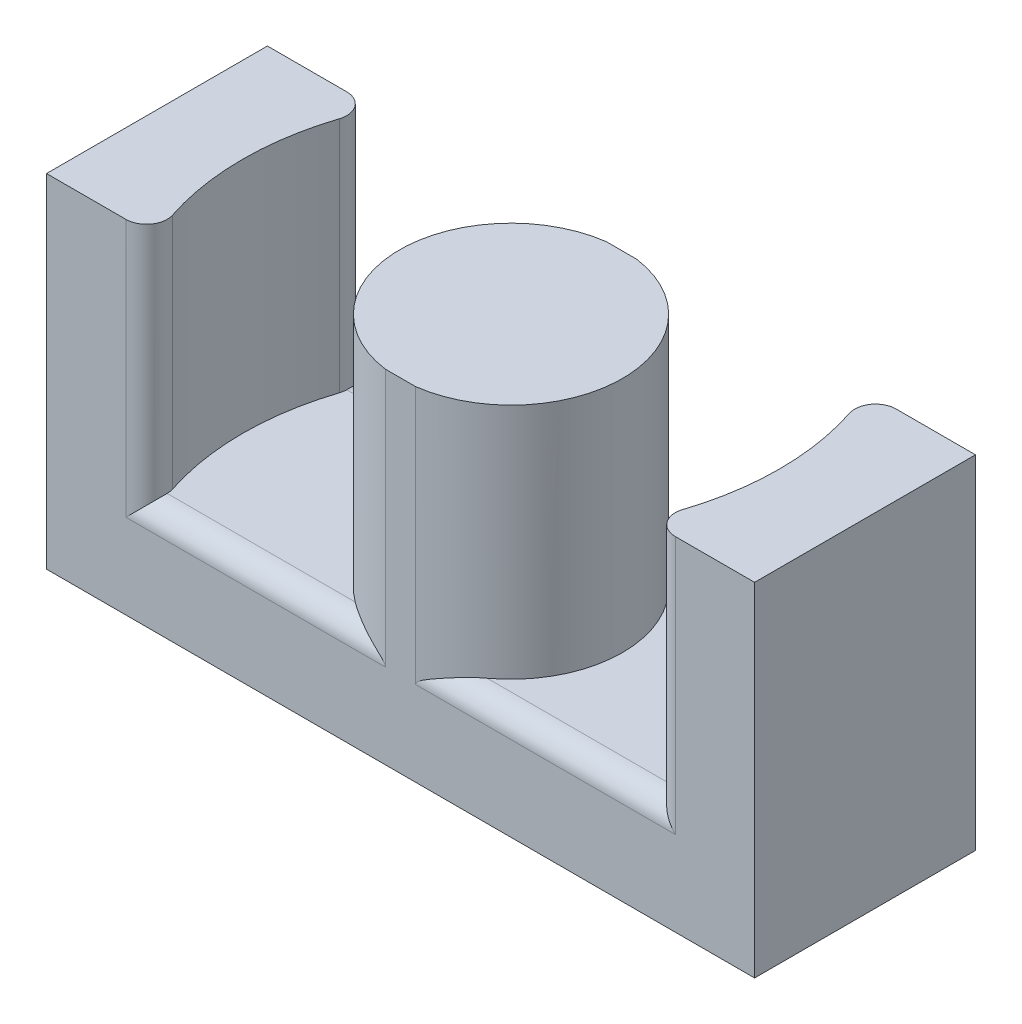
SolidWorks part; units mm, degrees
ref_plane "Front Plane" through (0, 0, 0) normal (0, 0, 1) x (1, 0, 0)
ref_plane "Top Plane" through (0, 0, 0) normal (0, 1, 0) x (1, 0, 0)
ref_plane "Right Plane" through (0, 0, 0) normal (1, 0, 0) x (0, 0, -1)
sketch "Sketch1" plane through (0, 0, 0) normal (0, 1, 0) x (1, 0, 0)
  line L0 (-22.3173, 0) -> (23.0727, 0) construction
  line L1 (11.8481, -5.35) -> (17.15, -5.35)
  line L2 (-17.15, 5.35) -> (-11.8481, 5.35)
  line L3 (-17.15, 5.35) -> (-17.15, -5.35)
  line L4 (-17.15, -5.35) -> (-11.8481, -5.35)
  line L5 (17.15, 5.35) -> (17.15, -5.35)
  line L6 (-17.15, 5.35) -> (-12.4102, 3.8714) construction
  line L7 (-17.15, -5.35) -> (-12.4102, -3.8714) construction
  line L8 (12.4102, -3.8714) -> (17.15, -5.35) construction
  line L9 (12.4102, 3.8714) -> (17.15, 5.35) construction
  line L10 (11.8481, 5.35) -> (17.15, 5.35)
  line L11 (-0.7331, 5.35) -> (0.7331, 5.35)
  line L12 (-5.155, 1.6081) -> (5.155, -1.6081) construction
  line L13 (-5.155, -1.6081) -> (5.155, 1.6081) construction
  line L14 (-0.7331, -5.35) -> (0.7331, -5.35)
  circle A0 centre (0, 0) radius 5.4
  arc A1 (-11.8481, 5.35) -> (-11.8481, -5.35) centre (0, 0) ccw
  arc A2 (11.8481, -5.35) -> (11.8481, 5.35) centre (0, 0) ccw
  dimension "D1" = 10.8
  dimension "D2" = 26
  dimension "D3" = 34.3
  dimension "D4" = 10.7
extrude "Boss-Extrude1" add sketch "Sketch1" along normal blind 11.5 contours A1 L2 L3 L4 | L14 A0 L11 | A2 L1 L5 L10
sketch "Sketch2" plane through (0, 0, 0) normal (0, -1, 0) x (1, 0, 0)
  line L1 (17.15, -5.35) -> (-17.15, -5.35)
  line L2 (17.15, -5.35) -> (17.15, 5.35)
  line L3 (17.15, 5.35) -> (-17.15, 5.35)
  line L4 (-17.15, -5.35) -> (-17.15, 5.35)
  line L5 (17.15, -5.35) -> (-17.15, 5.35) construction
  line L6 (17.15, 5.35) -> (-17.15, -5.35) construction
  point P0 (0, 0)
extrude "Boss-Extrude2" add sketch "Sketch2" along normal blind 5.1
sketch "Sketch3" plane through (0, 11.5, 0) normal (0, 1, 0) x (1, 0, 0)
  circle A0 centre (0, 0) radius 5.4 construction
  circle A1 centre (0, 0) radius 13 construction
  point P5 (-11.8481, 5.35)
  point P6 (11.8481, 5.35)
  dimension "D1" = 23.6962
fillet "Fillet1" radius 1 8 edges at (-11.8481, 5.75, 5.35) (-11.8481, 5.75, -5.35) (11.8481, 5.75, 5.35) (11.8481, 5.75, -5.35) (-6.2906, 0, -5.35) (6.2906, 0, -5.35) (6.2906, 0, 5.35) (-6.2906, 0, 5.35)
